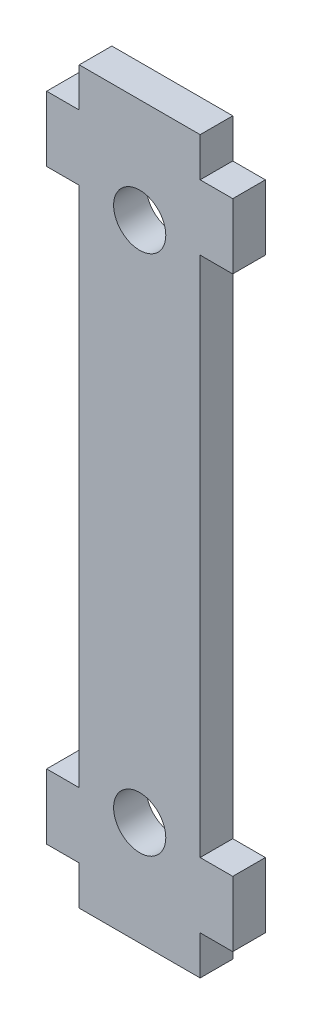
SolidWorks part; units mm, degrees
ref_plane "Front Plane" through (0, 0, 0) normal (1, 0, 0) x (0, 1, 0)
ref_plane "Top Plane" through (0, 0, 0) normal (0, 0, 1) x (0, 1, 0)
ref_plane "Right Plane" through (0, 0, 0) normal (0, 1, 0) x (-1, 0, 0)
sketch "Sketch1" plane through (0, 0, 0) normal (0, 0, 1) x (0, 1, 0)
  line L0 (-56, 14.27) -> (-50, 14.27) construction
  line L1 (-56, -14.27) -> (-50, -14.27) construction
  line L2 (-56, -9.27) -> (-56, 9.27)
  line L3 (-56, 14.27) -> (-50, 14.27) construction
  line L4 (56, -9.27) -> (56, 9.27)
  line L5 (-56, -14.27) -> (56, 14.27) construction
  line L6 (-56, 14.27) -> (56, -14.27) construction
  line L7 (-50, 14.27) -> (-50, 12.7411)
  line L8 (-50, 9.27) -> (-40, 9.27) construction
  line L9 (-40, 9.27) -> (-40, 10.1929)
  line L10 (0, -14.27) -> (0, 14.27) construction
  line L11 (56, 0) -> (-56, 0) construction
  line L12 (0, 14.27) -> (40, 14.27) construction
  line L13 (40, 9.27) -> (40, 14.27)
  line L14 (50, 9.27) -> (40, 9.27) construction
  line L15 (50, 14.27) -> (50, 9.27)
  line L16 (50, -14.27) -> (50, -9.27)
  line L17 (50, -9.27) -> (40, -9.27) construction
  line L18 (40, -9.27) -> (40, -10.1929)
  line L19 (-50, -9.27) -> (-40, -9.27) construction
  line L20 (-50, -14.27) -> (-50, -12.7411)
  line L21 (-40, -9.27) -> (-40, -10.1929)
  line L22 (-40, -14.27) -> (0, -14.27) construction
  line L23 (50, -14.27) -> (56, -14.27) construction
  line L24 (50, 14.27) -> (56, 14.27) construction
  line L25 (-50, -9.27) -> (-56, -9.27)
  line L26 (-40, -9.27) -> (40, -9.27)
  line L27 (56, 9.27) -> (50, 9.27)
  line L28 (-56, 9.27) -> (-56, 14.27) construction
  line L29 (-56, -14.27) -> (-56, -9.27) construction
  line L30 (-40, 14.27) -> (0, 14.27) construction
  line L31 (56, 9.27) -> (56, 14.27) construction
  line L32 (56, -14.27) -> (56, -9.27) construction
  line L33 (0, -14.27) -> (40, -14.27) construction
  line L34 (-50, -14.27) -> (-40, -14.27)
  line L35 (40, -14.27) -> (50, -14.27)
  line L36 (40, 14.27) -> (50, 14.27)
  line L37 (-50, 14.27) -> (-40, 14.27)
  line L38 (-50, 12.7411) -> (-50, 9.27)
  line L39 (-40, 10.1929) -> (-40, 14.27)
  line L40 (-40, 9.27) -> (-50, 9.27) construction
  line L41 (-50, 9.27) -> (-56, 9.27)
  line L42 (-50, -12.7411) -> (-50, -9.27)
  line L43 (-40, -10.1929) -> (-40, -14.27)
  line L44 (40, -10.1929) -> (40, -14.27)
  line L45 (40, -9.27) -> (50, -9.27) construction
  line L46 (50, -9.27) -> (56, -9.27)
  line L47 (50, 9.27) -> (40, 9.27) construction
  line L48 (40, 9.27) -> (-40, 9.27)
  point P0 (0, 0)
  point P13 (0, 0)
  point P16 (0, 0)
  dimension "D1" = 112
  dimension "D2" = 28.54
  dimension "D3" = 6
  dimension "D4" = 10
  dimension "D5" = 5
extrude "Boss-Extrude1" add sketch "Sketch1" along normal mid plane 5
sketch "Sketch3" plane through (0, 0, 2.5) normal (0, 0, 1) x (1, 0, 0)
  line L0 (0, -56) -> (0, 56) construction
  line L1 (0, -40) -> (0, 40)
  line L20 (-14.27, 40) -> (-9.27, 40)
  line L21 (-9.27, 40) -> (-9.27, -40)
  line L22 (-9.27, -40) -> (-14.27, -40)
  line L23 (-14.27, -40) -> (-14.27, -50)
  line L24 (-14.27, -50) -> (-9.27, -50)
  line L25 (-9.27, -50) -> (-9.27, -56)
  line L26 (-9.27, -56) -> (9.27, -56)
  line L27 (9.27, -56) -> (9.27, -50)
  line L28 (9.27, -50) -> (14.27, -50)
  line L29 (14.27, -50) -> (14.27, -40)
  line L30 (14.27, -40) -> (9.27, -40)
  line L31 (9.27, -40) -> (9.27, 40)
  line L32 (9.27, 40) -> (14.27, 40)
  line L33 (14.27, 40) -> (14.27, 50)
  line L34 (14.27, 50) -> (9.27, 50)
  line L35 (9.27, 50) -> (9.27, 56)
  line L36 (9.27, 56) -> (-9.27, 56)
  line L37 (-9.27, 56) -> (-9.27, 50)
  line L38 (-9.27, 50) -> (-14.27, 50)
  line L39 (-14.27, 50) -> (-14.27, 40)
  line L40 (-14.27, 40) -> (-9.27, 40)
  line L41 (-9.27, 40) -> (-9.27, -40)
  line L42 (-9.27, -40) -> (-14.27, -40)
  line L43 (-14.27, -40) -> (-14.27, -50)
  line L44 (-14.27, -50) -> (-9.27, -50)
  line L45 (-9.27, -50) -> (-9.27, -56)
  line L46 (-9.27, -56) -> (9.27, -56)
  line L47 (9.27, -56) -> (9.27, -50)
  line L48 (9.27, -50) -> (14.27, -50)
  line L49 (14.27, -50) -> (14.27, -40)
  line L50 (14.27, -40) -> (9.27, -40)
  line L51 (9.27, -40) -> (9.27, 40)
  line L52 (9.27, 40) -> (14.27, 40)
  line L53 (14.27, 40) -> (14.27, 50)
  line L54 (14.27, 50) -> (9.27, 50)
  line L55 (9.27, 50) -> (9.27, 56)
  line L56 (9.27, 56) -> (-9.27, 56)
  line L57 (-9.27, 56) -> (-9.27, 50)
  line L58 (-9.27, 50) -> (-14.27, 50)
  line L59 (-14.27, 50) -> (-14.27, 40)
  circle A0 centre (0, 40) radius 4
  circle A1 centre (0, -40) radius 4
  point P12 (0, 0)
  dimension "D2" = 8
  dimension "D3" = 80
  dimension "D1" = 0
extrude "Cut-Extrude2" cut sketch "Sketch3" against normal blind 5 contours A0 | A1
